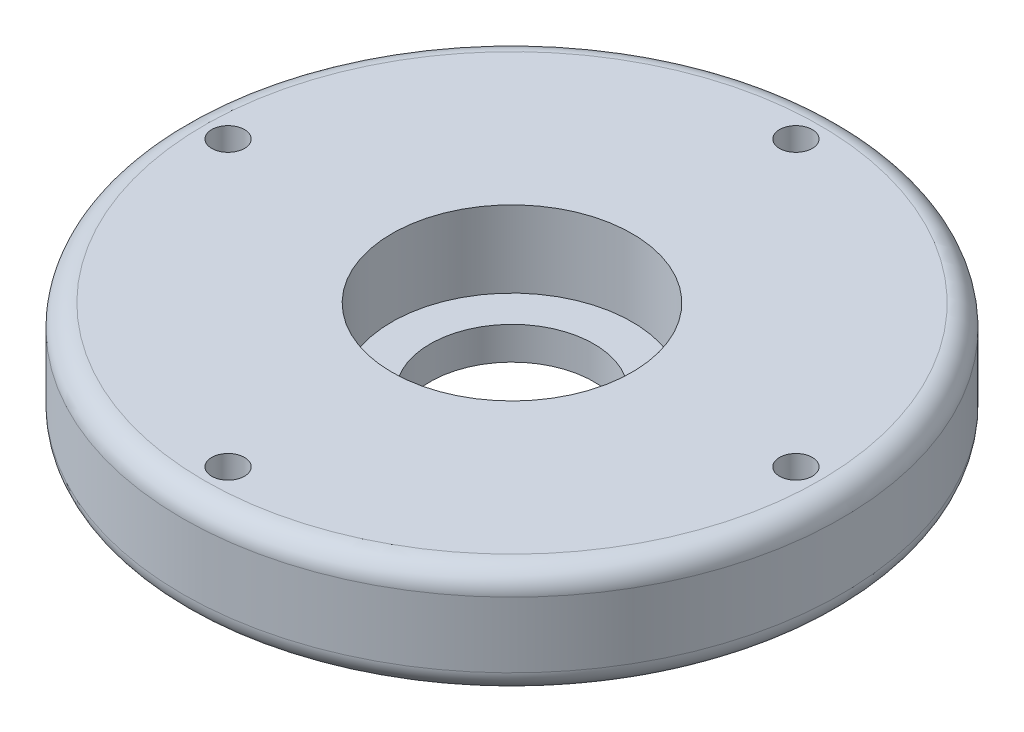
SolidWorks part; units mm, degrees
ref_plane "Front Plane" through (0, 0, 0) normal (0, 0, 1) x (1, 0, 0)
ref_plane "Top Plane" through (0, 0, 0) normal (0, 1, 0) x (1, 0, 0)
ref_plane "Right Plane" through (0, 0, 0) normal (1, 0, 0) x (0, 0, -1)
sketch "Sketch1" plane through (0, 0, 0) normal (0, 1, 0) x (1, 0, 0)
  circle A0 centre (0, 0) radius 30.18
  circle A1 centre (0, 0) radius 7.5
  dimension "D1" = 60.36
  dimension "D2" = 15
extrude "Boss-Extrude1" add sketch "Sketch1" along normal blind 10
sketch "Sketch2" plane through (0, 10, 0) normal (0, 1, 0) x (1, 0, 0)
  circle A0 centre (0, 26) radius 1.5
  circle A1 centre (26, 0) radius 1.5
  circle A2 centre (-26, 0) radius 1.5
  circle A3 centre (0, -26) radius 1.5
  circle A4 centre (0, 0) radius 26 construction
  point P11 (0, 0)
  dimension "D1" = 52
  dimension "D2" = 3
extrude "Cut-Extrude1" cut sketch "Sketch2" against normal through all
sketch "Sketch3" plane through (0, 10, 0) normal (0, 1, 0) x (1, 0, 0)
  circle A0 centre (0, 0) radius 11
  dimension "D1" = 22
extrude "Cut-Extrude2" cut sketch "Sketch3" against normal blind 7
fillet "Fillet1" radius 2 2 edges at (0, 0, 30.18) (0, 10, 30.18)
